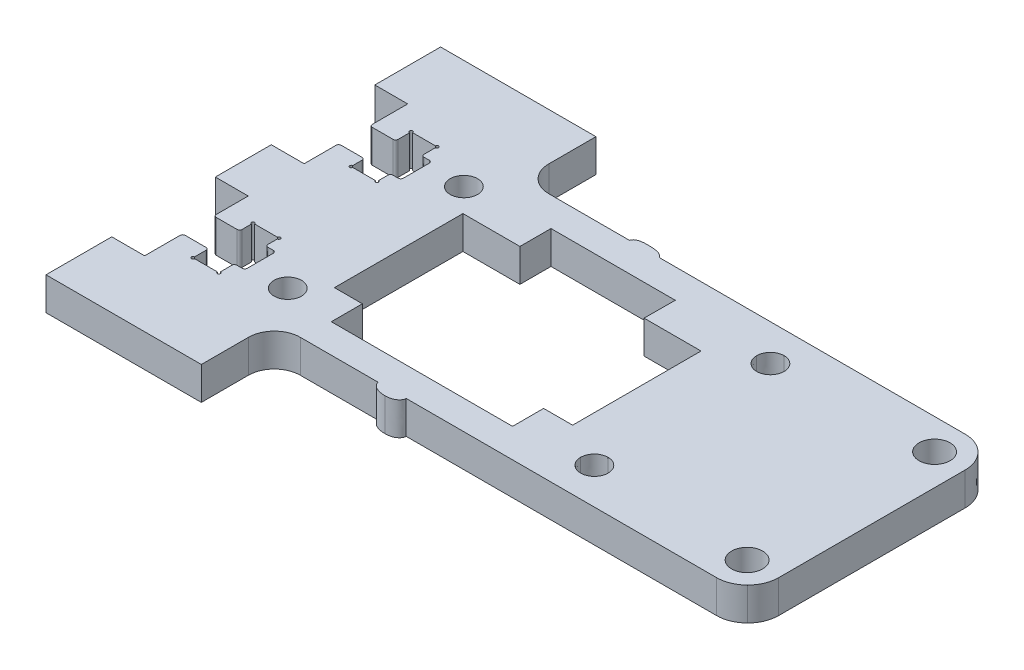
SolidWorks part; units mm, degrees
ref_plane "Front Plane" through (0, 0, 0) normal (0, 0, 1) x (1, 0, 0)
ref_plane "Top Plane" through (0, 0, 0) normal (0, 1, 0) x (1, 0, 0)
ref_plane "Right Plane" through (0, 0, 0) normal (1, 0, 0) x (0, 0, -1)
sketch "Sketch2" plane through (0, 0, 0) normal (0, 1, 0) x (1, 0, 0)
  line L0 (94.6268, 60.3088) -> (87.1105, 60.3088)
  line L1 (94.9178, 84.3088) -> (87.1105, 84.3088)
  line L2 (84.6105, 57.8088) -> (84.6105, 53.2588)
  line L3 (84.6105, 53.2588) -> (69.6105, 53.2588)
  line L4 (107.6105, 72.3088) -> (42.272, 72.3088) construction
  line L5 (84.6105, 86.8088) -> (84.6105, 91.3588)
  line L6 (84.6105, 91.3588) -> (69.6105, 91.3588)
  line L7 (69.6105, 85.0088) -> (69.6105, 91.3588)
  line L9 (76.5355, 62.5035) -> (76.5355, 67.9783) construction
  line L10 (77.7855, 62.5035) -> (75.2855, 62.5035) construction
  line L11 (69.6105, 69.6088) -> (69.6105, 59.6088) construction
  line L12 (75.4355, 61.7764) -> (75.5453, 61.7764)
  line L13 (69.6105, 75.0088) -> (72.7855, 75.0088)
  line L14 (72.7855, 75.0088) -> (72.7855, 78.0912)
  line L15 (72.7855, 85.0088) -> (69.6105, 85.0088)
  line L16 (77.7855, 61.9806) -> (77.7855, 61.9264)
  line L17 (77.7855, 67.3514) -> (77.7855, 67.4264)
  line L18 (75.4355, 67.5764) -> (75.5453, 67.5764)
  line L19 (73.0355, 78.3412) -> (75.0355, 78.3412)
  line L20 (75.2855, 78.0912) -> (75.2855, 77.2662)
  line L21 (75.5453, 77.0412) -> (77.6355, 77.0412)
  line L22 (77.7855, 77.2662) -> (77.7855, 78.0912)
  line L23 (78.0355, 78.3412) -> (78.5355, 78.3412)
  line L24 (78.7855, 78.5912) -> (78.7855, 81.0912)
  line L25 (78.5355, 81.3412) -> (78.0355, 81.3412)
  line L26 (77.7855, 81.5912) -> (77.7855, 82.6371)
  line L27 (77.6355, 82.8412) -> (75.5453, 82.8412)
  line L28 (75.2855, 82.6371) -> (75.2855, 81.5912)
  line L29 (75.0355, 81.3412) -> (73.0355, 81.3412)
  line L30 (72.7855, 81.5912) -> (72.7855, 85.0088)
  line L31 (77.7855, 82.1142) -> (75.2855, 82.1142) construction
  line L32 (76.5355, 82.1142) -> (76.5355, 76.6393) construction
  line L33 (75.2855, 67.3514) -> (75.2855, 67.4264)
  line L34 (75.2855, 82.6371) -> (75.2855, 82.6912)
  line L35 (75.2855, 77.2662) -> (75.2855, 77.1912)
  line L36 (75.4355, 77.0412) -> (75.5453, 77.0412)
  line L37 (77.7855, 77.2662) -> (77.7855, 77.1912)
  line L38 (77.7855, 82.6371) -> (77.7855, 82.6912)
  line L39 (75.4355, 82.8412) -> (75.5453, 82.8412)
  line L40 (75.2855, 61.9806) -> (75.2855, 61.9264)
  line L41 (72.7855, 63.0264) -> (72.7855, 59.6088)
  line L42 (75.0355, 63.2764) -> (73.0355, 63.2764)
  line L43 (75.2855, 61.9806) -> (75.2855, 63.0264)
  line L44 (77.6355, 61.7764) -> (75.5453, 61.7764)
  line L45 (77.7855, 63.0264) -> (77.7855, 61.9806)
  line L46 (78.5355, 63.2764) -> (78.0355, 63.2764)
  line L47 (78.7855, 66.0264) -> (78.7855, 63.5264)
  line L48 (78.0355, 66.2764) -> (78.5355, 66.2764)
  line L49 (77.7855, 67.3514) -> (77.7855, 66.5264)
  line L50 (75.5453, 67.5764) -> (77.6355, 67.5764)
  line L51 (75.2855, 66.5264) -> (75.2855, 67.3514)
  line L52 (73.0355, 66.2764) -> (75.0355, 66.2764)
  line L53 (72.7855, 59.6088) -> (69.6105, 59.6088)
  line L54 (72.7855, 69.6088) -> (72.7855, 66.5264)
  line L55 (69.6105, 69.6088) -> (72.7855, 69.6088)
  line L56 (69.6105, 53.2588) -> (69.6105, 59.6088)
  line L57 (69.6105, 69.6088) -> (69.6105, 75.0088)
  line L558 (104.8605, 66.1089) -> (104.8102, 66.1089)
  line L559 (104.8102, 66.1089) -> (104.8102, 63.1088)
  line L560 (104.8102, 63.1088) -> (87.3102, 63.1088)
  line L561 (87.3102, 63.1088) -> (87.3102, 66.1088)
  line L562 (87.3102, 66.1088) -> (84.6102, 66.1088)
  line L563 (84.6102, 66.1088) -> (84.6205, 78.5088)
  line L564 (84.6205, 78.5088) -> (90.1205, 78.5088)
  line L565 (90.1205, 78.5088) -> (90.1205, 81.5088)
  line L566 (90.1205, 81.5088) -> (102.1205, 81.5088)
  line L567 (102.1205, 81.5088) -> (102.1105, 78.5089)
  line L568 (102.1105, 78.5089) -> (107.6105, 78.5088)
  line L569 (107.6105, 78.5088) -> (107.6105, 66.1088)
  line L570 (107.6105, 66.1088) -> (104.8605, 66.1089)
  line L571 (97.2812, 60.3092) -> (127.3105, 60.3081)
  line L572 (130.3105, 63.3081) -> (130.3105, 81.3088)
  circle A0 centre (127.3105, 81.3586) radius 1.5001
  circle A1 centre (127.3105, 63.2587) radius 1.4999
  circle A2 centre (82.4103, 63.8086) radius 1.325
  circle A3 centre (82.4105, 80.8086) radius 1.3251
  arc A4 (73.0355, 81.3412) -> (72.7855, 81.5912) centre (73.0355, 81.5912) cw
  arc A5 (73.0355, 78.3412) -> (72.7855, 78.0912) centre (73.0355, 78.0912) ccw
  arc A6 (75.0355, 78.3412) -> (75.2855, 78.0912) centre (75.0355, 78.0912) cw
  arc A7 (75.2855, 81.5912) -> (75.0355, 81.3412) centre (75.0355, 81.5912) cw
  arc A8 (78.0355, 81.3412) -> (77.7855, 81.5912) centre (78.0355, 81.5912) cw
  arc A9 (77.7855, 78.0912) -> (78.0355, 78.3412) centre (78.0355, 78.0912) cw
  arc A10 (78.5355, 78.3412) -> (78.7855, 78.5912) centre (78.5355, 78.5912) ccw
  arc A11 (78.7855, 81.0912) -> (78.5355, 81.3412) centre (78.5355, 81.0912) ccw
  arc A12 (77.7855, 82.6912) -> (77.6355, 82.8412) centre (77.7855, 82.8412) ccw
  arc A13 (75.4355, 82.8412) -> (75.2855, 82.6912) centre (75.2855, 82.8412) ccw
  arc A14 (75.2855, 77.1912) -> (75.4355, 77.0412) centre (75.2855, 77.0412) ccw
  arc A15 (77.6355, 77.0412) -> (77.7855, 77.1912) centre (77.7855, 77.0412) ccw
  arc A16 (77.6355, 67.5764) -> (77.7855, 67.4264) centre (77.7855, 67.5764) cw
  arc A17 (75.2855, 67.4264) -> (75.4355, 67.5764) centre (75.2855, 67.5764) cw
  arc A18 (75.4355, 61.7764) -> (75.2855, 61.9264) centre (75.2855, 61.7764) cw
  arc A19 (77.7855, 61.9264) -> (77.6355, 61.7764) centre (77.7855, 61.7764) cw
  arc A20 (78.7855, 63.5264) -> (78.5355, 63.2764) centre (78.5355, 63.5264) cw
  arc A21 (78.5355, 66.2764) -> (78.7855, 66.0264) centre (78.5355, 66.0264) cw
  arc A22 (77.7855, 66.5264) -> (78.0355, 66.2764) centre (78.0355, 66.5264) ccw
  arc A23 (78.0355, 63.2764) -> (77.7855, 63.0264) centre (78.0355, 63.0264) ccw
  arc A24 (75.2855, 63.0264) -> (75.0355, 63.2764) centre (75.0355, 63.0264) ccw
  arc A25 (75.0355, 66.2764) -> (75.2855, 66.5264) centre (75.0355, 66.5264) ccw
  arc A26 (73.0355, 66.2764) -> (72.7855, 66.5264) centre (73.0355, 66.5264) cw
  arc A27 (73.0355, 63.2764) -> (72.7855, 63.0264) centre (73.0355, 63.0264) ccw
  arc A28 (84.6105, 86.8088) -> (87.1105, 84.3088) centre (87.1105, 86.8088) ccw
  arc A29 (84.6105, 57.8088) -> (87.1105, 60.3088) centre (87.1105, 57.8088) cw
  spline S285 degree 3 poles (94.6268, 60.3088) (94.6269, 60.3088) (94.7497, 59.5124) (96.1106, 59.5126) knots 0 0 0 0 0.058824 0.058824 0.058824 0.058824
  spline S286 degree 3 poles (96.1106, 59.5126) (97.2245, 59.5127) (97.4504, 60.3092) (97.2812, 60.3092) knots 0.058824 0.058824 0.058824 0.058824 0.117647 0.117647 0.117647 0.117647
  spline S287 degree 3 poles (127.3105, 60.3081) (128.1061, 60.3081) (128.8691, 60.6241) (129.4317, 61.1867) knots 0.176471 0.176471 0.176471 0.176471 0.235294 0.235294 0.235294 0.235294
  spline S288 degree 3 poles (129.4317, 61.1867) (129.9943, 61.7493) (130.3105, 62.5124) (130.3105, 63.3081) knots 0.235294 0.235294 0.235294 0.235294 0.294118 0.294118 0.294118 0.294118
  spline S289 degree 3 poles (130.3105, 81.3088) (130.3105, 82.1044) (129.9943, 82.8675) (129.4317, 83.4301) knots 0.352941 0.352941 0.352941 0.352941 0.411765 0.411765 0.411765 0.411765
  spline S290 degree 3 poles (129.4317, 83.4301) (128.8691, 83.9927) (128.1061, 84.3088) (127.3105, 84.3088) knots 0.411765 0.411765 0.411765 0.411765 0.470588 0.470588 0.470588 0.470588
  spline S291 degree 2 poles (127.3105, 84.3088) (106.1437, 84.3088) (98.0308, 84.3088) knots 0.470588 0.470588 0.470588 0.529412 0.529412 0.529412
  spline S292 degree 3 poles (98.0308, 84.3088) (97.3832, 84.3088) (97.9635, 84.8127) (96.1105, 84.8127) knots 0.529412 0.529412 0.529412 0.529412 0.588235 0.588235 0.588235 0.588235
  spline S293 degree 2 poles (96.1105, 84.8127) (94.9984, 84.8127) (94.9178, 84.3088) knots 0.588235 0.588235 0.588235 0.647059 0.647059 0.647059
  spline S304 degree 3 poles (110.6853, 63.8086) (110.6853, 63.0768) (111.2786, 62.4835) (112.0102, 62.4835) knots 0 0 0 0 0.2 0.2 0.2 0.2
  spline S305 degree 3 poles (112.0102, 62.4835) (112.7421, 62.4835) (113.3353, 63.0768) (113.3353, 63.8085) knots 0.2 0.2 0.2 0.2 0.4 0.4 0.4 0.4
  spline S306 degree 3 poles (113.3353, 63.8085) (113.3353, 64.5403) (112.7421, 65.1335) (112.0104, 65.1335) knots 0.4 0.4 0.4 0.4 0.6 0.6 0.6 0.6
  spline S307 degree 3 poles (112.0104, 65.1335) (111.2786, 65.1335) (110.6853, 64.5403) (110.6853, 63.8086) knots 0.6 0.6 0.6 0.6 1 1 1 1
  spline S308 degree 3 poles (110.6853, 80.8085) (110.6853, 80.0767) (111.2786, 79.4834) (112.0102, 79.4834) knots 0 0 0 0 0.2 0.2 0.2 0.2
  spline S309 degree 3 poles (112.0102, 79.4834) (112.7421, 79.4834) (113.3353, 80.0767) (113.3353, 80.8084) knots 0.2 0.2 0.2 0.2 0.4 0.4 0.4 0.4
  spline S310 degree 3 poles (113.3353, 80.8084) (113.3353, 81.5402) (112.7421, 82.1334) (112.0104, 82.1334) knots 0.4 0.4 0.4 0.4 0.6 0.6 0.6 0.6
  spline S311 degree 3 poles (112.0104, 82.1334) (111.2786, 82.1334) (110.6853, 81.5402) (110.6853, 80.8085) knots 0.6 0.6 0.6 0.6 1 1 1 1
  point P116 (84.6105, 84.3088)
  point P119 (84.6105, 60.3088)
  dimension "D14" = 0.25
  dimension "D17" = 0.3
  dimension "D18" = 0.3
  dimension "D19" = 0.3
  dimension "D20" = 0.3
  dimension "D21" = 38.1
  dimension "D35" = 2.5
  dimension "D4" = 3.175
  dimension "D5" = 15
  dimension "D6" = 15
  dimension "D7" = 7.05
  dimension "D8" = 7.05
  dimension "D9" = 10
  dimension "D10" = 2.5
  dimension "D11" = 6
  dimension "D12" = 2.5
  dimension "D13" = 5.8
  dimension "D15" = 2.5
  dimension "D16" = 2.5
  dimension "D23" = 12.4
  dimension "D24" = 12.4
  dimension "D25" = 12
  dimension "D26" = 17.5
  dimension "D27" = 3
  dimension "D28" = 3
  dimension "D29" = 5.5
  dimension "D30" = 5.5
  dimension "D31" = 2.75
  dimension "D32" = 2.7
  dimension "D33" = 2.8
  dimension "D34" = 2.8
  dimension "D36" = 6.35
  dimension "D37" = 5.8
  dimension "D38" = 5.8
  dimension "D39" = 5.7999
extrude "Boss-Extrude1" add sketch "Sketch2" along normal blind 3.175
